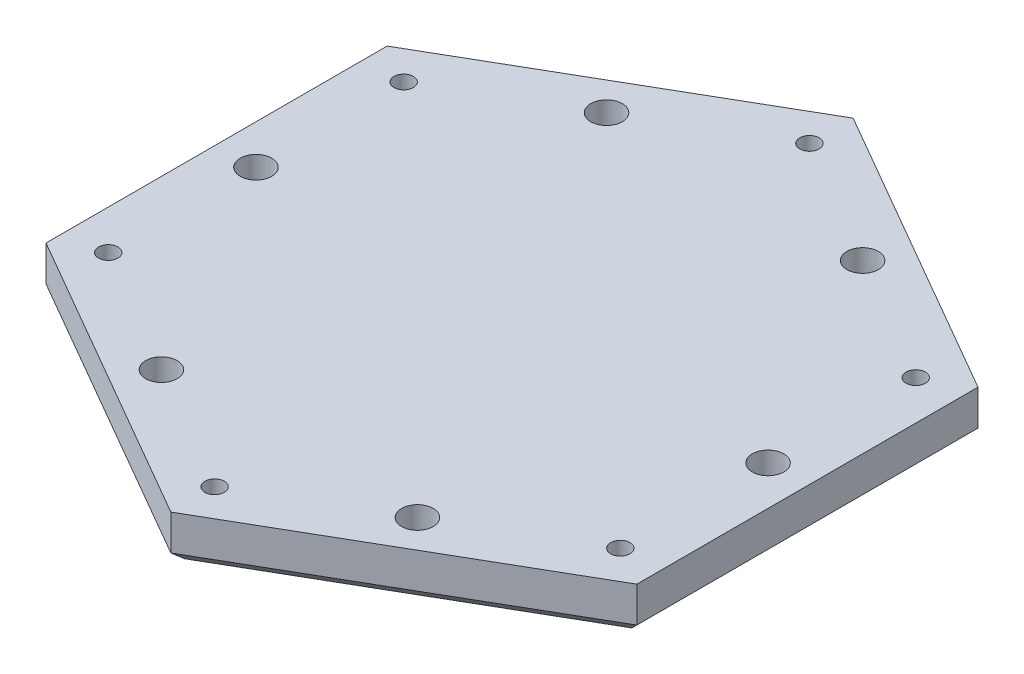
SolidWorks part; units mm, degrees
ref_plane "前基準面" through (0, 0, 0) normal (0, 0, 1) x (1, 0, 0)
ref_plane "上基準面" through (0, 0, 0) normal (0, 1, 0) x (1, 0, 0)
ref_plane "右基準面" through (0, 0, 0) normal (1, 0, 0) x (0, 0, -1)
ref_plane "平面1"
sketch "草圖1" plane through (0, 0, 0) normal (0, 1, 0) x (-1, 0, 0)
  line L0 (0, -86.6025) -> (-75, -43.3013)
  line L1 (-75, -43.3013) -> (-75, 43.3013)
  line L2 (-75, 43.3013) -> (0, 86.6025)
  line L3 (0, 86.6025) -> (75, 43.3013)
  line L4 (75, 43.3013) -> (75, -43.3013)
  line L5 (75, -43.3013) -> (0, -86.6025)
  dimension "D1" = 150
extrude "擠出1" add sketch "草圖1" along normal blind 12
chamfer "倒角1" distance 3 distance2 3 6 edges at (37.5, 0, 64.9519) (75, 0, 0) (-37.5, 0, 64.9519) (-75, 0, 0) (-37.5, 0, -64.9519) (37.5, 0, -64.9519)
sketch "草圖2" plane through (0, 12, 0) normal (0, 1, 0) x (-1, 0, 0)
  circle A0 centre (32.5, -56.5) radius 4
  circle A1 centre (-32.5, -56.5) radius 4
  circle A2 centre (65, 0) radius 4
  circle A3 centre (32.5, 56.5) radius 4
  circle A4 centre (-32.5, 56.5) radius 4
  circle A5 centre (-65, 0) radius 4
  dimension "D5" = 8
  dimension "D6" = 8
  dimension "D7" = 8
  dimension "D8" = 8
  dimension "D9" = 8
  dimension "D10" = 8
  dimension "D1" = 65
  dimension "D2" = 113
  dimension "D3" = 65
  dimension "D4" = 65
extrude "擠出2" cut sketch "草圖2" against normal blind 12 contours A4 | A3 | A5 | A1 | A0 | A2
hole_wizard "孔1" positions "草圖4" profile "草圖3" legacy
sketch "草圖4" plane through (0, 12, 0) normal (0, 1, 0) x (1, 0, 0)
  point P1 (0, 75.5)
  point P2 (-65, 37.5)
  point P3 (65, 37.5)
  point P4 (-65, -37.5)
  point P5 (65, -37.5)
  point P6 (0, -75.5)
sketch "草圖3" plane through (0, 12, -75.5) normal (1, 0, 0) x (0, 0, 1)
  line L0 (0, 0) -> (0, 18.5772)
  line L1 (0, 18.5772) -> (2.4585, 17.1)
  line L2 (2.4585, 17.1) -> (2.4585, 0)
  line L4 (2.4585, 0) -> (0, 0)
  line L6 (0, 18.5772) -> (-2.4585, 17.1) construction
  line L7 (0, -4.2442) -> (0, 117.3081) construction
  dimension "直徑" = 4.917
  dimension "深度" = 17.1
  dimension "導頭角度" = 118
cosmetic thread "裝飾螺紋線1" parameters "D1"=12, "D2"=6.294
cosmetic thread "裝飾螺紋線2" parameters "D1"=12, "D2"=6.294
cosmetic thread "裝飾螺紋線3" parameters "D1"=12, "D2"=6.294
cosmetic thread "裝飾螺紋線4" parameters "D1"=12, "D2"=6.294
cosmetic thread "裝飾螺紋線5" parameters "D1"=12, "D2"=6.294
cosmetic thread "裝飾螺紋線6" parameters "D1"=12, "D2"=6.294
